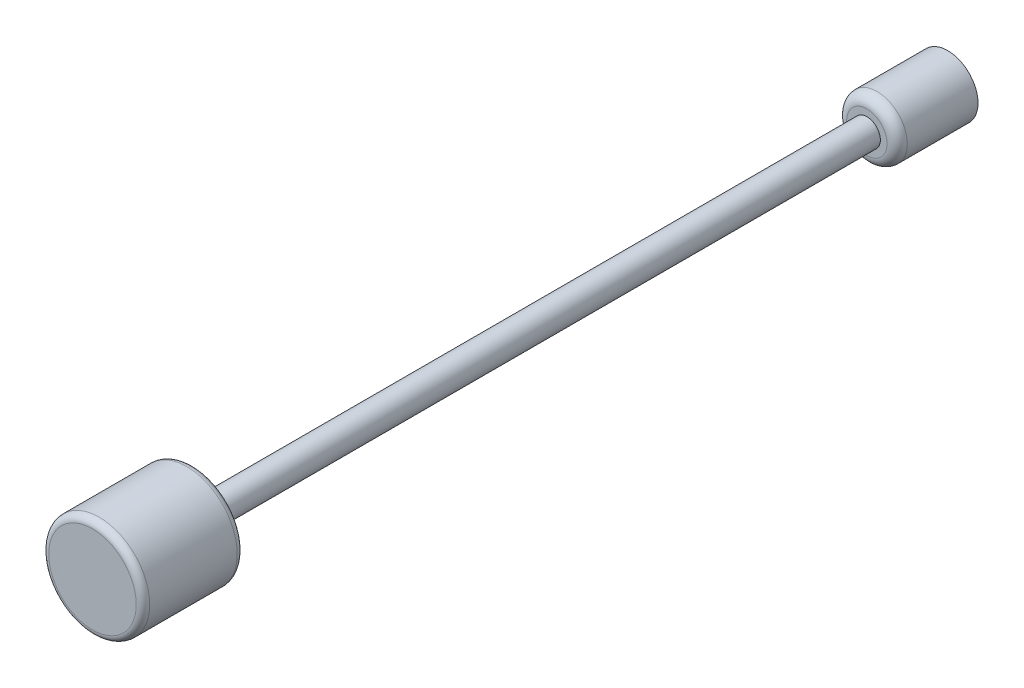
SolidWorks part; units mm, degrees
ref_plane "Front Plane" through (0, 0, 0) normal (0, 0, 1) x (1, 0, 0)
ref_plane "Top Plane" through (0, 0, 0) normal (0, 1, 0) x (1, 0, 0)
ref_plane "Right Plane" through (0, 0, 0) normal (1, 0, 0) x (0, 0, -1)
sketch "Sketch1" plane through (0, 0, 0) normal (0, 0, 1) x (1, 0, 0)
  circle A0 centre (1107.9507, 105.911) radius 3
  circle A1 centre (1107.9507, 105.911) radius 4.5
extrude "Boss-Extrude1" add sketch "Sketch1" along normal blind 10
sketch "Sketch2" plane through (0, 0, 10) normal (0, 0, 1) x (1, 0, 0)
  circle A1 centre (1107.9507, 105.911) radius 4.5
  circle A2 centre (1107.9507, 105.911) radius 4.5
  dimension "D1" = 0
extrude "Boss-Extrude2" add sketch "Sketch2" along normal blind 2
sketch "Sketch3" plane through (0, 0, 12) normal (0, 0, 1) x (1, 0, 0)
  circle A0 centre (1107.9507, 105.911) radius 2
extrude "Boss-Extrude3" add sketch "Sketch3" along normal blind 100
sketch "Sketch4" plane through (0, 0, 112) normal (0, 0, 1) x (1, 0, 0)
  circle A0 centre (1107.9507, 105.911) radius 7.5
extrude "Boss-Extrude4" add sketch "Sketch4" along normal blind 15
fillet "Fillet1" radius 1 2 edges at (1115.4507, 105.911, 112) (1115.4507, 105.911, 127)
fillet "Fillet2" radius 1.5 1 edges at (1112.4507, 105.911, 12)
